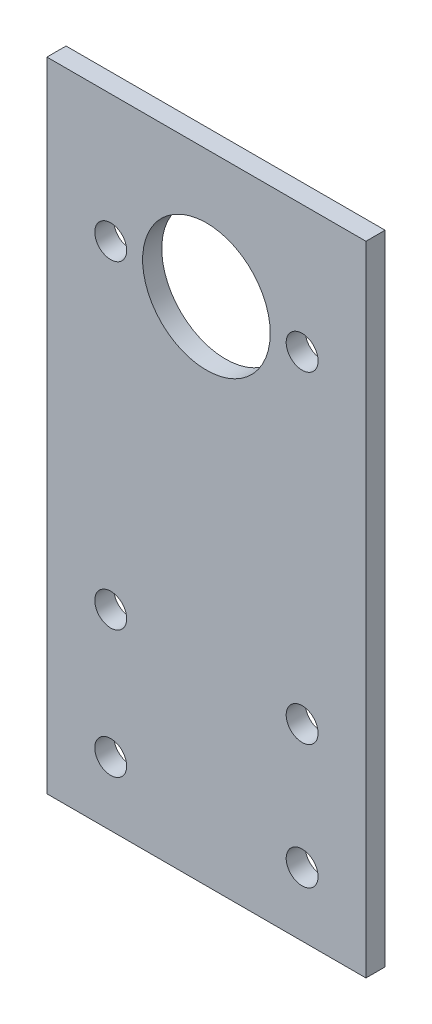
SolidWorks part; units mm, degrees
ref_plane "Płaszczyzna przednia" through (0, 0, 0) normal (0, 0, 1) x (1, 0, 0)
ref_plane "Płaszczyzna górna" through (0, 0, 0) normal (0, 1, 0) x (1, 0, 0)
ref_plane "Płaszczyzna prawa" through (0, 0, 0) normal (1, 0, 0) x (0, 0, -1)
sketch "Szkic1" plane through (0, 0, 0) normal (0, 0, 1) x (1, 0, 0)
  line L1 (-16.7838, 56.0092) -> (33.2162, 56.0092)
  line L2 (-16.7838, 56.0092) -> (-16.7838, -43.9908)
  line L3 (-16.7838, -43.9908) -> (33.2162, -43.9908)
  line L4 (33.2162, 56.0092) -> (33.2162, -43.9908)
  circle A0 centre (23.2162, -33.9908) radius 2.5
  circle A1 centre (-6.7838, -33.9908) radius 2.5
  circle A2 centre (23.2162, -14.5243) radius 2.5
  circle A3 centre (-6.7838, -13.9908) radius 2.5
  dimension "D3" = 5
  dimension "D4" = 5
  dimension "D5" = 5
  dimension "D6" = 5
  dimension "D1" = 50
  dimension "D2" = 100
  dimension "D7" = 30
  dimension "D8" = 30
  dimension "D9" = 10
  dimension "D10" = 10
  dimension "D11" = 10
  dimension "D12" = 10
  dimension "D13" = 20
extrude "Dodanie-wyciągnięcie1" add sketch "Szkic1" along normal blind 3
sketch "Szkic2" plane through (0, 0, 3) normal (0, 0, 1) x (1, 0, 0)
  line L0 (-16.7838, -43.9908) -> (33.2162, -43.9908) construction
  line L1 (-16.7838, 56.0092) -> (-16.7838, -43.9908) construction
  circle A0 centre (8.2162, 36.0092) radius 10
  circle A1 centre (-6.7838, 36.0092) radius 2.5
  circle A2 centre (23.2162, 36.0092) radius 2.5
  dimension "D2" = 20
  dimension "D6" = 5
  dimension "D7" = 5
  dimension "D1" = 30
  dimension "D3" = 15
  dimension "D4" = 80
  dimension "D5" = 25
extrude "Wytnij-wyciągnięcie1" cut sketch "Szkic2" against normal blind 3
